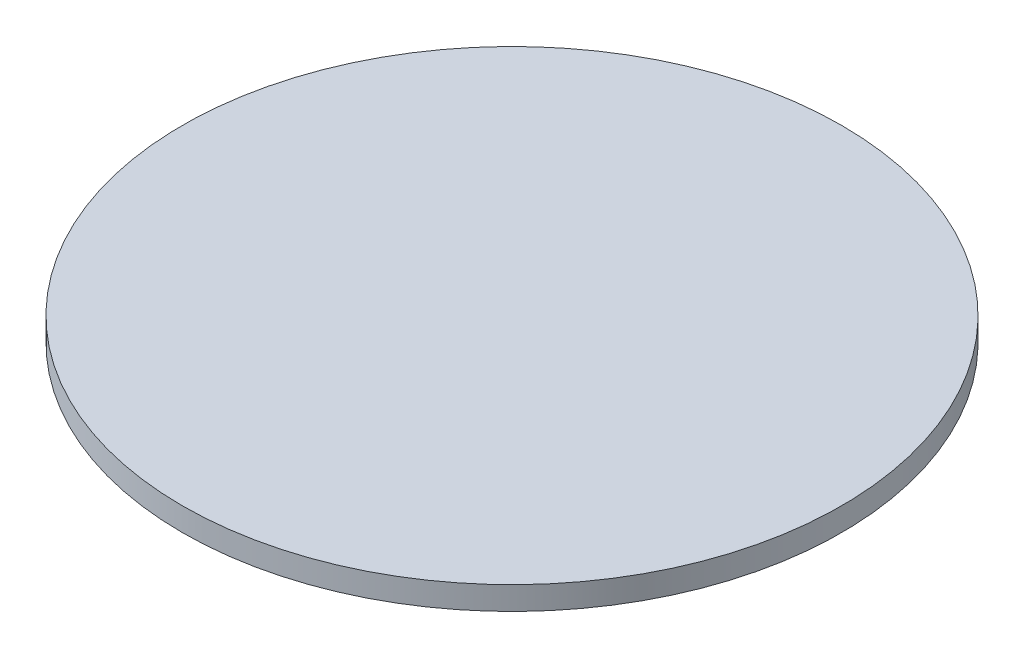
SolidWorks part; units mm, degrees
material "Balsa"
ref_plane "Front Plane" through (0, 0, 0) normal (0, 0, 1) x (1, 0, 0)
ref_plane "Top Plane" through (0, 0, 0) normal (0, 1, 0) x (1, 0, 0)
ref_plane "Right Plane" through (0, 0, 0) normal (1, 0, 0) x (0, 0, -1)
sketch "Sketch1" plane through (0, 0, 0) normal (0, 1, 0) x (1, 0, 0)
  circle A0 centre (0, 0) radius 95
  dimension "D1" = 95
extrude "Boss-Extrude1" add sketch "Sketch1" along normal blind 6.7 contours A0
equation "\"Ring inner radius\"= 80mm"
equation "\"D1@Sketch1\" = \"Bottom ring outer radius\""
equation "\"Heart cable hole radius\"= 3.5mm"
equation "\"Dogbone radius\"= 3mm"
equation "\"Tree side stock thickness\"= 6.7mm"
equation "\"Ring stock thickness\"= 6.7mm"
equation "\"D1@Boss-Extrude1\"= \"Ring stock thickness\""
equation "\"Tree teeth\"= 15mm"
equation "\"Tree slot\"= 15mm"
equation "\"Bottom ring outer radius\"= \"Ring inner radius\" + \"Tree teeth\""
equation "\"Cut-Extrude Tolerance\"= 5mm"
equation "\"Ring outer radius\"= \"Ring inner radius\" + \"Tree slot\" + 10"
